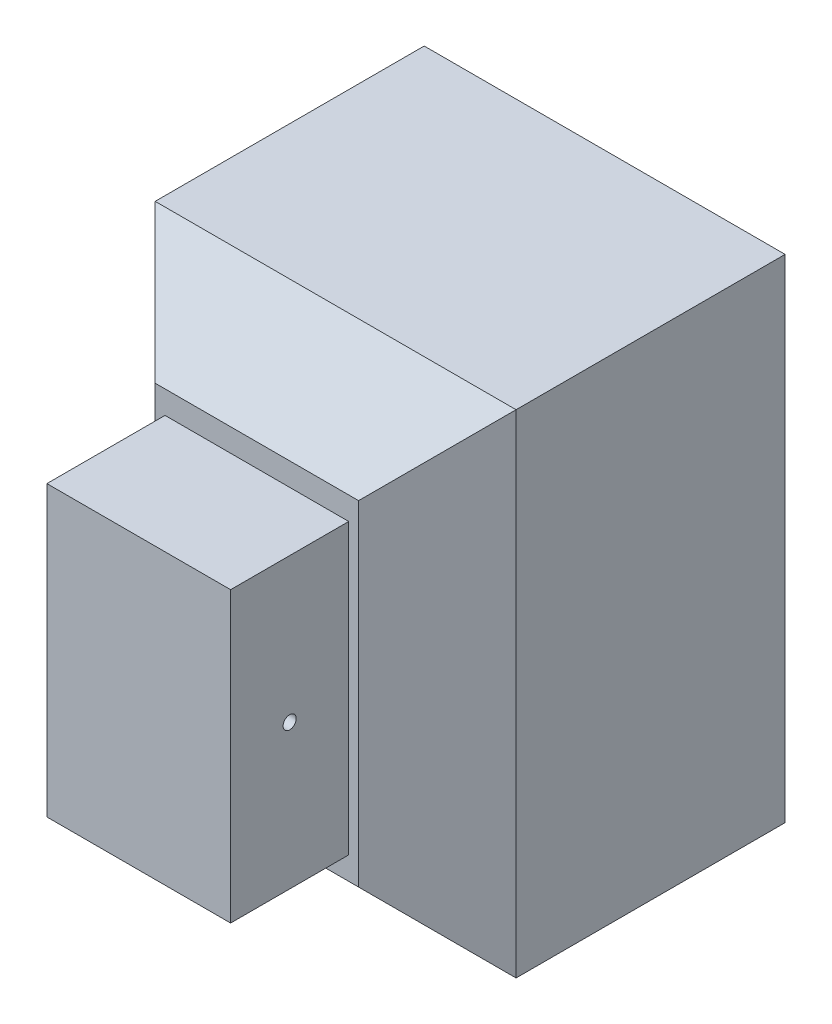
SolidWorks part; units mm, degrees
ref_plane "Front Plane" through (0, 0, 0) normal (1, 0, 0) x (0, 1, 0)
ref_plane "Top Plane" through (0, 0, 0) normal (0, 0, 1) x (0, 1, 0)
ref_plane "Right Plane" through (0, 0, 0) normal (0, 1, 0) x (-1, 0, 0)
sketch "Sketch1" plane through (0, 0, 0) normal (1, 0, 0) x (0, 1, 0)
  line L1 (-32.1033, 29.2989) -> (42.8967, 29.2989)
  line L2 (-32.1033, 29.2989) -> (-32.1033, -35.7011)
  line L3 (-32.1033, -35.7011) -> (42.8967, -35.7011)
  line L4 (42.8967, 29.2989) -> (42.8967, -35.7011)
  dimension "D1" = 75
  dimension "D2" = 65
extrude "Boss-Extrude1" add sketch "Sketch1" along normal blind 55
sketch "Sketch2" plane through (0, 0, 29.2989) normal (0, 0, 1) x (1, 0, 0)
  line L0 (0, 42.8967) -> (55, -32.1033) construction
  line L1 (13.5, 27.3967) -> (41.5, 27.3967)
  line L2 (13.5, 27.3967) -> (13.5, -16.6033)
  line L3 (13.5, -16.6033) -> (41.5, -16.6033)
  line L4 (41.5, 27.3967) -> (41.5, -16.6033)
  line L5 (27.5, 42.8967) -> (27.5, -32.1033) construction
  line L6 (55, 42.8967) -> (0, 42.8967) construction
  line L7 (55, -32.1033) -> (0, -32.1033) construction
  line L8 (13.5, 5.3967) -> (41.5, 5.3967) construction
  point P16 (27.5, 5.3967)
  point P17 (27.5, 5.3967)
  point P18 (0, 0)
  dimension "D1" = 44
  dimension "D2" = 28
extrude "Boss-Extrude2" add sketch "Sketch2" along normal blind 18
chamfer "Chamfer1" distance 12 angle 45 8 edges at (27.5, -32.1033, 29.2989) (0, 5.3967, 29.2989) (27.5, 42.8967, 29.2989) (55, 5.3967, 29.2989) (27.5, -32.1033, -35.7011) (0, 5.3967, -35.7011) (27.5, 42.8967, -35.7011) (55, 5.3967, -35.7011)
sketch "Sketch3" plane through (41.5, 0, 0) normal (1, 0, 0) x (0, 1, 0)
  circle A0 centre (5.3967, 38.2989) radius 1
  dimension "D1" = 2
extrude "Cut-Extrude1" cut sketch "Sketch3" against normal through all both and the other way through all
